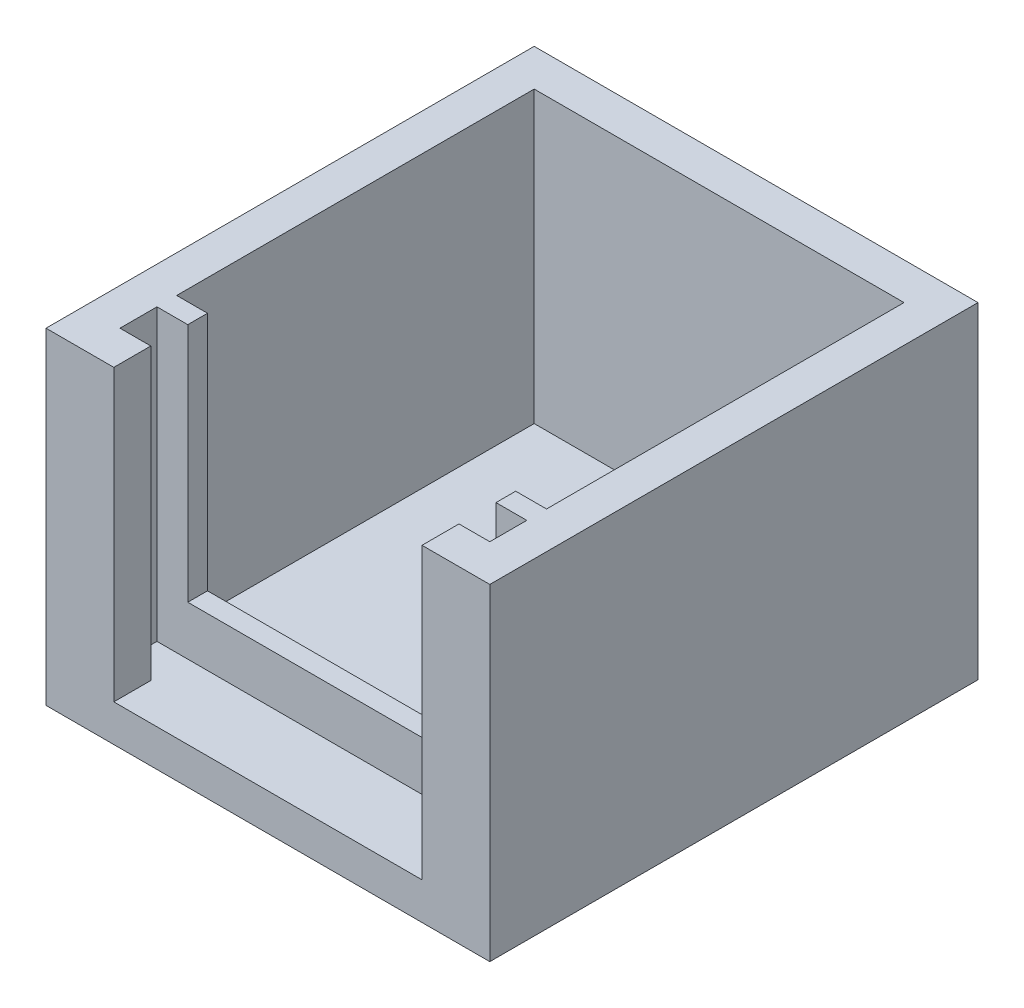
SolidWorks part; units mm, degrees
ref_plane "Front Plane" through (0, 0, 0) normal (0, 0, 1) x (1, 0, 0)
ref_plane "Top Plane" through (0, 0, 0) normal (0, 1, 0) x (1, 0, 0)
ref_plane "Right Plane" through (0, 0, 0) normal (1, 0, 0) x (0, 0, -1)
sketch "Sketch1" plane through (0, 0, 0) normal (0, 1, 0) x (1, 0, 0)
  line L0 (-48.6117, -16.6154) -> (-48.6117, 24.0378) construction
  line L1 (-48.6117, 16.1433) -> (-18.6117, 16.1433)
  line L2 (-48.6117, 16.1433) -> (-48.6117, -12.8567)
  line L3 (-48.6117, -12.8567) -> (-18.6117, -12.8567)
  line L4 (-18.6117, 16.1433) -> (-18.6117, -12.8567)
  line L5 (-18.6117, -14.4567) -> (-48.6117, -14.4567)
  line L6 (-18.6117, -14.4567) -> (-18.6117, -17.4567)
  line L7 (-18.6117, -17.4567) -> (-48.6117, -17.4567)
  line L8 (-48.6117, -14.4567) -> (-48.6117, -17.4567)
  line L9 (-51.6117, 19.1433) -> (-15.6117, 19.1433)
  line L10 (-51.6117, 19.1433) -> (-51.6117, -20.4567)
  line L11 (-51.6117, -20.4567) -> (-15.6117, -20.4567)
  line L12 (-15.6117, 19.1433) -> (-15.6117, -20.4567)
  line L13 (-21.1117, -17.4567) -> (-21.1117, -20.4567)
  line L14 (-46.1117, -17.4567) -> (-46.1117, -20.4567)
  dimension "D1" = 1.6
  dimension "D2" = 3
  dimension "D3" = 29
  dimension "D4" = 30
  dimension "D5" = 3
  dimension "D6" = 3
  dimension "D7" = 3
  dimension "D8" = 3
  dimension "D9" = 2.5
  dimension "D10" = 2.5
extrude "Boss-Extrude1" add sketch "Sketch1" along normal blind 23.5 contours L8 L0 L2 L9 L10 L11 L14 L7 | L0 L5 L6 L7 L13 L11 L12 L9 L1 L4 L3
sketch "Sketch2" plane through (0, 0, 0) normal (0, -1, 0) x (1, 0, 0)
  line L1 (-51.6117, 20.4567) -> (-15.6117, 20.4567)
  line L2 (-51.6117, 20.4567) -> (-51.6117, -19.1433)
  line L3 (-51.6117, -19.1433) -> (-15.6117, -19.1433)
  line L4 (-15.6117, 20.4567) -> (-15.6117, -19.1433)
extrude "Boss-Extrude2" add sketch "Sketch2" along normal blind 3
sketch "Sketch3" plane through (0, 23.5, 0) normal (0, 1, 0) x (1, 0, 0)
  line L1 (-51.6117, 19.1433) -> (-15.6117, 19.1433)
  line L2 (-51.6117, 19.1433) -> (-51.6117, -20.4567)
  line L3 (-51.6117, -20.4567) -> (-15.6117, -20.4567)
  line L4 (-15.6117, 19.1433) -> (-15.6117, -20.4567)
sketch "Sketch5" plane through (0, 0, 14.4567) normal (0, 0, 1) x (1, 0, 0)
  line L1 (-46.1117, 23.5) -> (-21.1117, 23.5)
  line L2 (-46.1117, 23.5) -> (-46.1117, 0)
  line L3 (-46.1117, 0) -> (-21.1117, 0)
  line L4 (-21.1117, 23.5) -> (-21.1117, 0)
  line L5 (-46.1117, 0) -> (-21.1117, 0)
  line L6 (-46.1117, 0) -> (-46.1117, 4)
  line L7 (-46.1117, 4) -> (-21.1117, 4)
  line L8 (-21.1117, 0) -> (-21.1117, 4)
  line M7 (-18.6117, 23.5) -> (-48.6117, 23.5)
  dimension "D1" = 4
extrude "Cut-Extrude3" cut sketch "Sketch5" against normal up to next contours L2 L7 L4 M7
